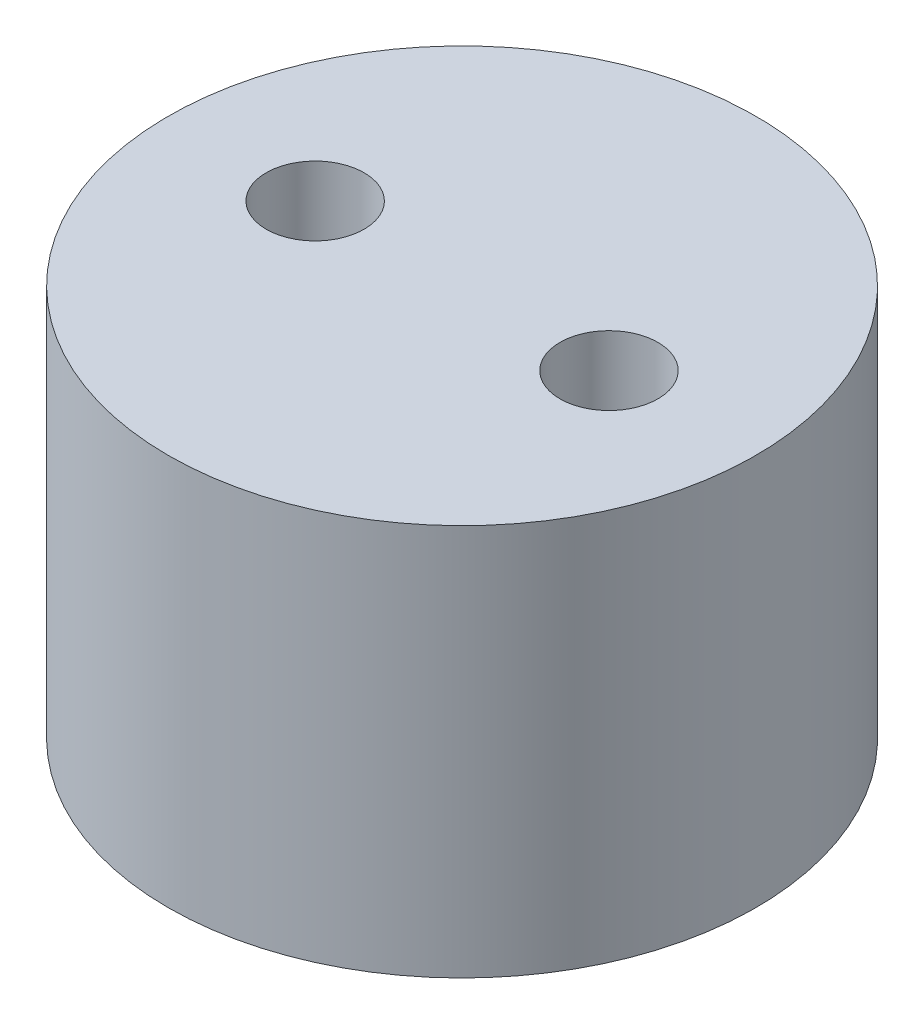
SolidWorks part; units mm, degrees
ref_plane "Front Plane" through (0, 0, 0) normal (0, 0, 1) x (1, 0, 0)
ref_plane "Top Plane" through (0, 0, 0) normal (0, 1, 0) x (1, 0, 0)
ref_plane "Right Plane" through (0, 0, 0) normal (1, 0, 0) x (0, 0, -1)
sketch "Sketch1" plane through (0, 0, 0) normal (0, 1, 0) x (1, 0, 0)
  circle A0 centre (0, 0) radius 15
  circle A1 centre (-7.5, 0) radius 2.5
  circle A2 centre (7.5, 0) radius 2.5
  point P7 (0, 0)
  dimension "D1" = 30
  dimension "D2" = 5
  dimension "D3" = 15
  dimension "D4" = 7.5
extrude "Boss-Extrude1" add sketch "Sketch1" along normal blind 20
